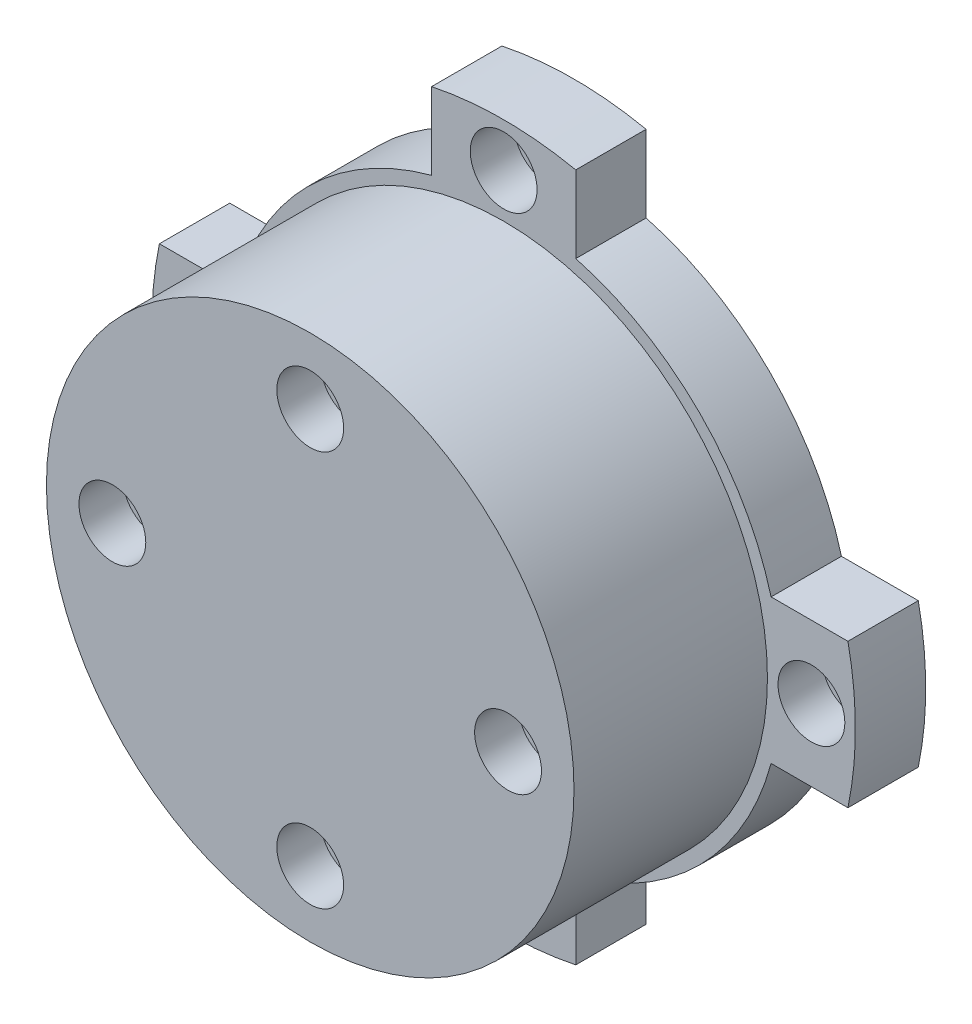
SolidWorks part; units mm, degrees
ref_plane "Front Plane" through (0, 0, 0) normal (0, 0, 1) x (1, 0, 0)
ref_plane "Top Plane" through (0, 0, 0) normal (0, 1, 0) x (1, 0, 0)
ref_plane "Right Plane" through (0, 0, 0) normal (1, 0, 0) x (0, 0, -1)
sketch "Sketch1" plane through (0, 0, 0) normal (0, 0, 1) x (1, 0, 0)
  line L0 (0, 0) -> (0, 40) construction
  line L1 (0, 0) -> (40, 0) construction
  line L2 (-8.2, 39.1505) -> (-8.2, 30.414)
  line L3 (8.2, 39.1505) -> (8.2, 30.414)
  line L4 (39.1505, -8.2) -> (30.414, -8.2)
  line L5 (39.1505, 8.2) -> (30.414, 8.2)
  line L6 (-8.2, -39.1505) -> (-8.2, -30.414)
  line L7 (8.2, -39.1505) -> (8.2, -30.414)
  line L8 (-39.1505, 8.2) -> (-30.414, 8.2)
  line L9 (-39.1505, -8.2) -> (-30.414, -8.2)
  arc A0 (-39.1505, 8.2) -> (-39.1505, -8.2) centre (0, 0) ccw
  arc A1 (-8.2, 30.414) -> (-30.414, 8.2) centre (0, 0) ccw
  arc A2 (8.2, 39.1505) -> (-8.2, 39.1505) centre (0, 0) ccw
  arc A3 (-8.2, -39.1505) -> (8.2, -39.1505) centre (0, 0) ccw
  arc A4 (39.1505, -8.2) -> (39.1505, 8.2) centre (0, 0) ccw
  arc A5 (30.414, 8.2) -> (8.2, 30.414) centre (0, 0) ccw
  arc A6 (8.2, -30.414) -> (30.414, -8.2) centre (0, 0) ccw
  arc A7 (-30.414, -8.2) -> (-8.2, -30.414) centre (0, 0) ccw
  point P10 (0, 0)
  point P11 (0, 0)
  point P12 (0, 0)
  point P25 (0, 0)
  point P26 (0, 0)
  point P27 (0, 0)
  point P28 (0, 0)
  dimension "D1" = 80
  dimension "D2" = 63
  dimension "D3" = 16.4
  dimension "D4" = 4
extrude "Boss-Extrude1" add sketch "Sketch1" along normal blind 8
sketch "Sketch2" plane through (0, 0, 8) normal (0, 0, 1) x (1, 0, 0)
  circle A0 centre (0, 0) radius 30
  dimension "D1" = 60
extrude "Boss-Extrude2" add sketch "Sketch2" along normal blind 22
sketch "Sketch3" plane through (0, 0, 8) normal (0, 0, 1) x (1, 0, 0)
  line L0 (-35, 0) -> (35, 0) construction
  circle A0 centre (0, 0) radius 35 construction
  circle A1 centre (0, 35) radius 3.8
  circle A2 centre (35, 0) radius 3.8
  circle A3 centre (0, -35) radius 3.8
  circle A4 centre (-35, 0) radius 3.8
  point P14 (0, 0)
  dimension "D1" = 7.6
  dimension "D2" = 70
  dimension "D3" = 4
extrude "Cut-Extrude1" cut sketch "Sketch3" against normal blind 5
sketch "Sketch4" plane through (0, 0, 30) normal (0, 0, 1) x (1, 0, 0)
  line L0 (-22.5, 0) -> (22.5, 0) construction
  circle A0 centre (0, 0) radius 22.5 construction
  circle A1 centre (0, 22.5) radius 3.8
  circle A2 centre (22.5, 0) radius 3.8
  circle A3 centre (0, -22.5) radius 3.8
  circle A4 centre (-22.5, 0) radius 3.8
  point P14 (0, 0)
  dimension "D1" = 7.6
  dimension "D2" = 45
  dimension "D3" = 4
extrude "Cut-Extrude2" cut sketch "Sketch4" against normal blind 5
